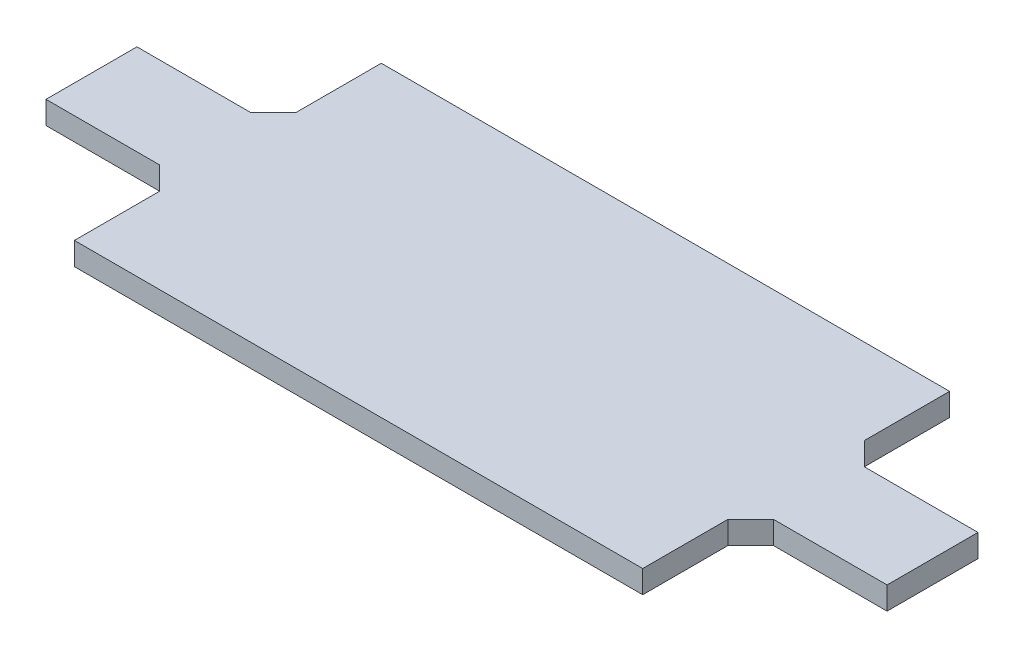
SolidWorks part; units mm, degrees
ref_plane "Front Plane" through (0, 0, 0) normal (0, 0, 1) x (1, 0, 0)
ref_plane "Top Plane" through (0, 0, 0) normal (0, 1, 0) x (1, 0, 0)
ref_plane "Right Plane" through (0, 0, 0) normal (1, 0, 0) x (0, 0, -1)
sketch "Sketch1" plane through (0, 0, 0) normal (0, 1, 0) x (1, 0, 0)
  line L0 (-157.1181, 0) -> (151.6204, 0) construction
  line L1 (125, -20) -> (125, -67.5)
  line L2 (-125, 67.5) -> (125, 67.5)
  line L3 (-125, 67.5) -> (-125, 20)
  line L4 (-125, -67.5) -> (125, -67.5)
  line L5 (125, 67.5) -> (125, 20)
  line L6 (-125, 67.5) -> (125, -67.5) construction
  line L7 (-125, -67.5) -> (125, 67.5) construction
  line L8 (125, -20) -> (185, -20)
  line L10 (125, 20) -> (185, 20)
  line L11 (185, -20) -> (185, 20)
  line L12 (0, 135.8222) -> (0, -137.3098) construction
  line L13 (-125, 20) -> (-185, 20)
  line L14 (-185, -20) -> (-185, 20)
  line L15 (-125, -20) -> (-185, -20)
  line L16 (-125, -20) -> (-125, -67.5)
  point P3 (0, 0)
  dimension "D1" = 250
  dimension "D2" = 135
  dimension "D3" = 40
  dimension "D4" = 60
extrude "Boss-Extrude1" add sketch "Sketch1" along normal blind 10
chamfer "Chamfer1" distance 10 angle 45 4 edges at (125, 5, 20) (125, 5, -20) (-125, 5, 20) (-125, 5, -20)
